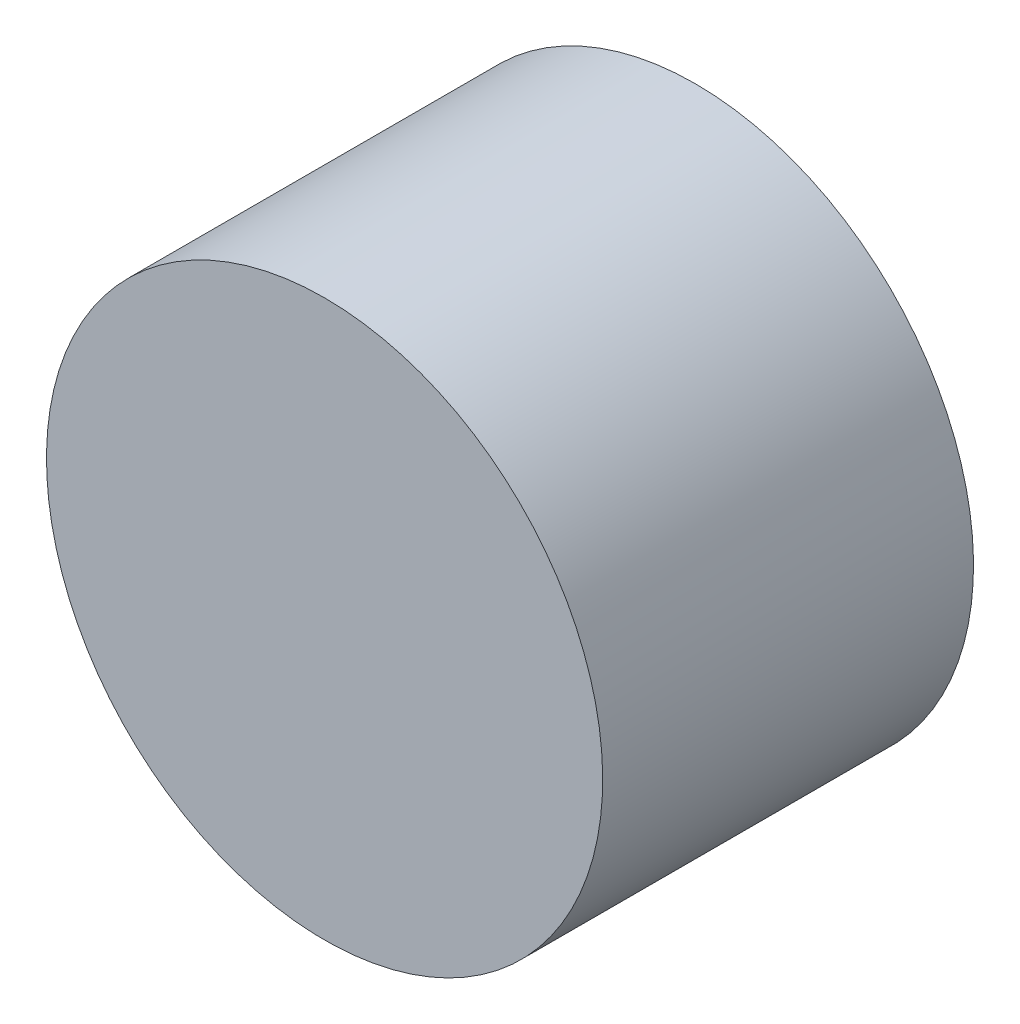
SolidWorks part; units mm, degrees
ref_plane "Plan de face" through (0, 0, 0) normal (0, 0, 1) x (1, 0, 0)
ref_plane "Plan de dessus" through (0, 0, 0) normal (0, 1, 0) x (1, 0, 0)
ref_plane "Plan de droite" through (0, 0, 0) normal (1, 0, 0) x (0, 0, -1)
sketch "Esquisse1" plane through (0, 0, 0) normal (1, 0, 0) x (0, 0, -1)
  line L0 (18.9402, 0) -> (-43.742, 0) construction
  line L1 (-38, 0) -> (-38, 28.5)
  line L2 (-38, 28.5) -> (0, 28.5)
  line L3 (0, 28.5) -> (0, 8)
  line L4 (0, 8) -> (-20, 8)
  line L5 (-20, 8) -> (-20, 0)
  line L6 (-20, 0) -> (-38, 0)
  dimension "D1" = 38
  dimension "D2" = 20
  dimension "D3" = 16
  dimension "D4" = 57
revolve "Révolution1" add sketch "Esquisse1" angle 360 about L6
